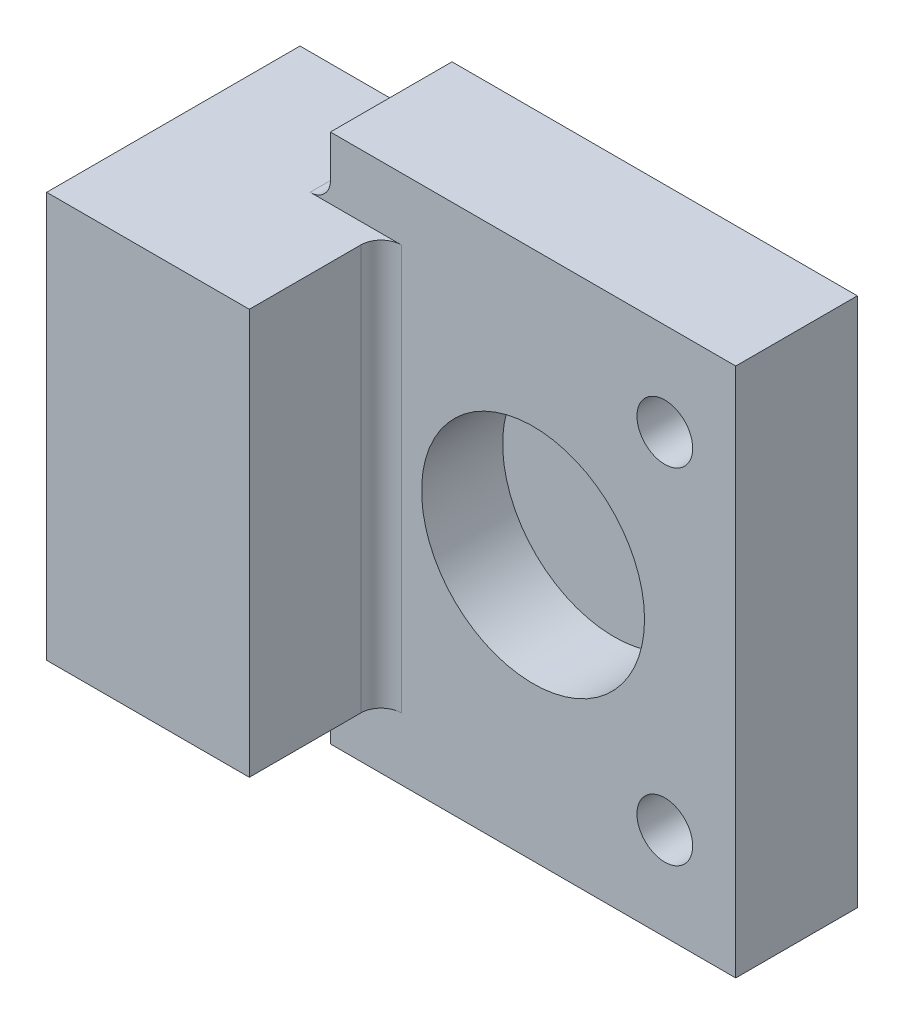
SolidWorks part; units mm, degrees
ref_plane "Front Plane" through (0, 0, 0) normal (0, 0, 1) x (1, 0, 0)
ref_plane "Top Plane" through (0, 0, 0) normal (0, 1, 0) x (1, 0, 0)
ref_plane "Right Plane" through (0, 0, 0) normal (1, 0, 0) x (0, 0, -1)
sketch "Sketch1" plane through (0, 0, 0) normal (0, 0, 1) x (1, 0, 0)
  line L1 (20, 26.15) -> (-20, 26.15)
  line L2 (20, 26.15) -> (20, -26.15)
  line L3 (20, -26.15) -> (-20, -26.15)
  line L4 (-20, 26.15) -> (-20, -26.15)
  line L5 (20, 26.15) -> (-20, -26.15) construction
  line L6 (20, -26.15) -> (-20, 26.15) construction
  circle A0 centre (13, 16.9975) radius 2.75
  circle A1 centre (13, -16.9975) radius 2.75
  point P0 (0, 0)
  dimension "D1" = 52.3
  dimension "D6" = 7
  dimension "D3" = 5.5
  dimension "D2" = 40
  dimension "D5" = 7
extrude "Boss-Extrude1" add sketch "Sketch1" along normal blind 12
sketch "Sketch2" plane through (0, 0, 12) normal (0, 0, 1) x (1, 0, 0)
  circle A0 centre (0, 0) radius 11
  dimension "D1" = 22
extrude "Cut-Extrude1" cut sketch "Sketch2" against normal blind 8
ref_plane "Plane1" through (-15, 0, 0) normal (-1, 0, 0) x (0, 0, 1)
sketch "Sketch6" plane through (-15, 0, 0) normal (-1, 0, 0) x (0, 0, 1)
  line L0 (0, 26.15) -> (0, -26.15) construction
  line L1 (0, 20) -> (25, 20)
  line L2 (0, 20) -> (0, -20)
  line L3 (0, -20) -> (25, -20)
  line L4 (25, 20) -> (25, -20)
  point P6 (0, 0)
  dimension "D1" = 40
  dimension "D2" = 25
extrude "Boss-Extrude3" add sketch "Sketch6" along normal blind 20
fillet "Fillet1" radius 2 2 edges at (-20, 20, 6) (-20, -20, 6)
fillet "Fillet2" radius 2 1 edges at (-15, 0, 12)
sketch "Sketch7" plane through (0, -20, 0) normal (0, -1, 0) x (1, 0, 0)
  line L0 (-35, 0) -> (-35, 25) construction
  line L1 (-35, 25) -> (-15, 25) construction
  circle A0 centre (-25, 15) radius 4
  dimension "D3" = 8
  dimension "D1" = 10
  dimension "D2" = 10
extrude "Cut-Extrude2" cut sketch "Sketch7" against normal blind 35
